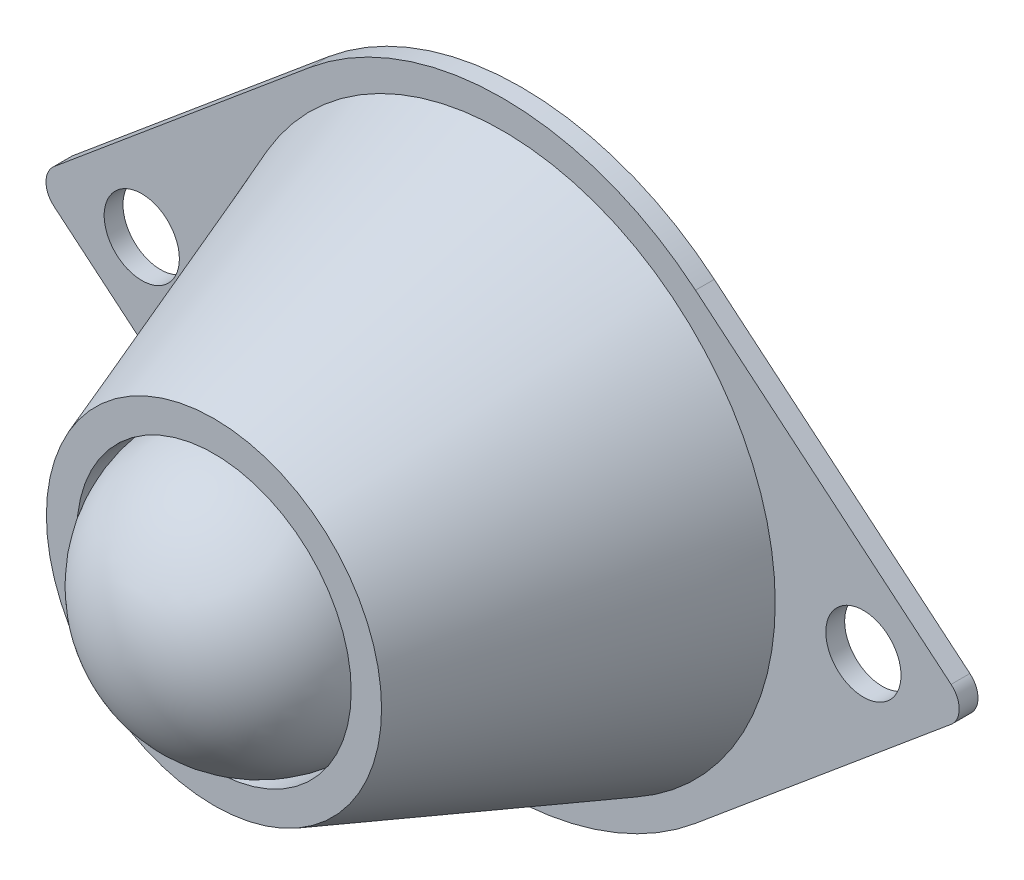
SolidWorks part; units mm, degrees
ref_plane "Front Plane" through (0, 0, 0) normal (0, 0, 1) x (1, 0, 0)
ref_plane "Top Plane" through (0, 0, 0) normal (0, 1, 0) x (1, 0, 0)
ref_plane "Right Plane" through (0, 0, 0) normal (1, 0, 0) x (0, 0, -1)
sketch "Sketch1" plane through (0, 0, 0) normal (0, 0, 1) x (1, 0, 0)
  line L3 (-23.8528, 0.9209) -> (-10.2585, 12.2786)
  line L4 (-23.8528, -0.9209) -> (-10.2585, -12.2786)
  line L8 (23.8528, -0.9209) -> (10.2585, -12.2786)
  line L9 (23.8528, 0.9209) -> (10.2585, 12.2786)
  arc A0 (-10.2585, -12.2786) -> (10.2585, -12.2786) centre (0, 0) ccw
  arc A1 (-23.8528, 0.9209) -> (-23.8528, -0.9209) centre (-23.0834, 0) ccw
  circle A2 centre (-19.19, 0) radius 2
  arc A3 (23.8528, 0.9209) -> (23.8528, -0.9209) centre (23.0834, 0) cw
  circle A4 centre (19.19, 0) radius 2
  arc A5 (10.2585, 12.2786) -> (-10.2585, 12.2786) centre (0, 0) ccw
  point P1 (-24.2834, 0)
  point P4 (24.2834, 0)
  point P6 (0, 0)
  point P17 (0, 0)
  dimension "D1" = 32
  dimension "D2" = 48.5668
extrude "Boss-Extrude1" add sketch "Sketch1" along normal blind 1
sketch "Sketch2" plane through (0, 0, 1) normal (0, 0, 1) x (1, 0, 0)
  circle A0 centre (0, 0) radius 14.5
  dimension "D1" = 29
extrude "Boss-Extrude7" add sketch "Sketch2" along normal blind 15.35 draft 20
sketch "Sketch5" plane through (0, 0, 16.35) normal (0, 0, 1) x (1, 0, 0)
  circle A0 centre (0, 0) radius 7.3
extrude "Cut-Extrude1" cut sketch "Sketch5" against normal blind 2.4
sketch "Sketch6" plane through (0, 0, 13.95) normal (0, 0, 1) x (1, 0, 0)
  line L0 (0, -7.3) -> (0, 7.3)
  circle A0 centre (0, 0) radius 7.3 construction
  arc A1 (0, 7.3) -> (0, -7.3) centre (0, 0) ccw
  point P7 (0, 0)
revolve "Revolve3" add sketch "Sketch6" angle 360 about L0
